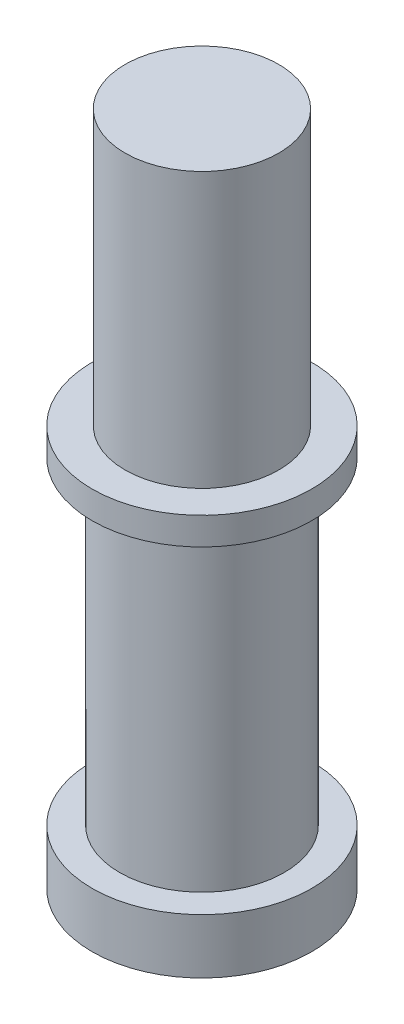
SolidWorks part; units mm, degrees
ref_plane "Front Plane" through (0, 0, 0) normal (0, 0, 1) x (1, 0, 0)
ref_plane "Top Plane" through (0, 0, 0) normal (0, 1, 0) x (1, 0, 0)
ref_plane "Right Plane" through (0, 0, 0) normal (1, 0, 0) x (0, 0, -1)
sketch "Sketch2" plane through (0, 0, 0) normal (0, 1, 0) x (1, 0, 0)
  circle A0 centre (0, 0) radius 2
  dimension "D1" = 4
extrude "Boss-Extrude1" add sketch "Sketch2" along normal blind 1
sketch "Sketch3" plane through (0, 1, 0) normal (0, 1, 0) x (1, 0, 0)
  circle A0 centre (0, 0) radius 1.5
extrude "Boss-Extrude2" add sketch "Sketch3" along normal blind 5.8
sketch "Sketch4" plane through (0, 6.8, 0) normal (0, 1, 0) x (1, 0, 0)
  circle A0 centre (0, 0) radius 2
extrude "Boss-Extrude3" add sketch "Sketch4" along normal blind 0.5
sketch "Sketch5" plane through (0, 7.3, 0) normal (0, 1, 0) x (1, 0, 0)
  circle A0 centre (0, 0) radius 1.4
extrude "Boss-Extrude4" add sketch "Sketch5" along normal blind 5
